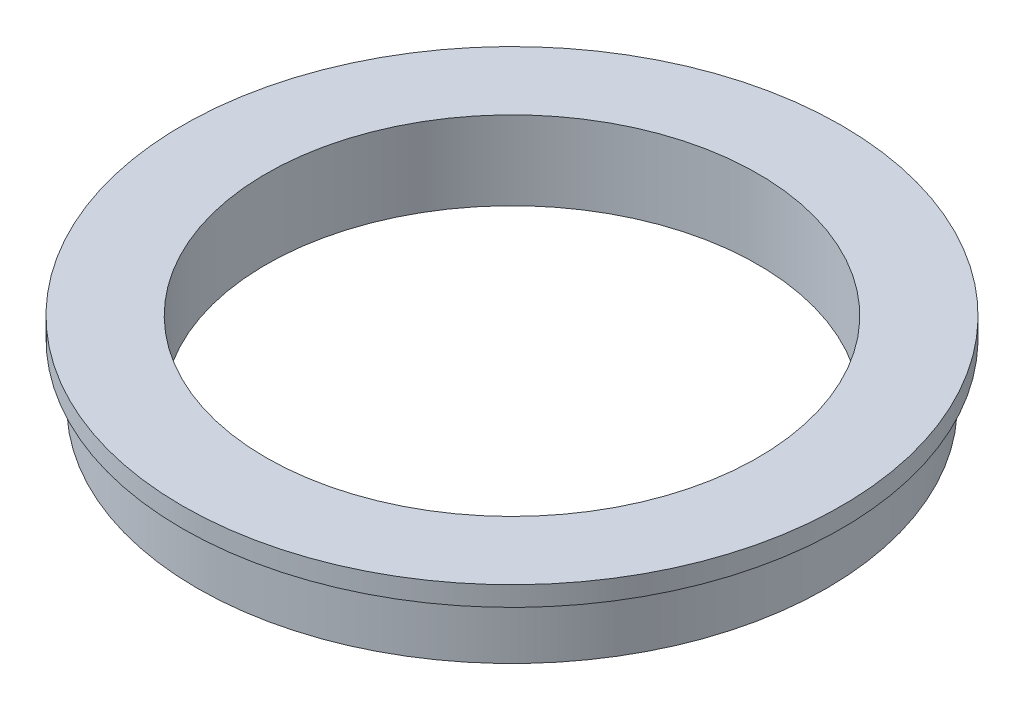
SolidWorks part; units mm, degrees
material "铸造不锈钢"
ref_plane "前视基准面" through (0, 0, 0) normal (0, 0, 1) x (1, 0, 0)
ref_plane "上视基准面" through (0, 0, 0) normal (0, 1, 0) x (1, 0, 0)
ref_plane "右视基准面" through (0, 0, 0) normal (1, 0, 0) x (0, 0, -1)
other "Configuration Table"
sketch "草图1" plane through (0, 0, 0) normal (0, 1, 0) x (1, 0, 0)
  circle A0 centre (0, 0) radius 16
  circle A1 centre (0, 0) radius 12.5
  point P5 (0, -0.2883)
  dimension "D1" = 32
  dimension "D2" = 25
extrude "凸台-拉伸1" add sketch "草图1" along normal blind 4
sketch "草图2" plane through (0, 4, 0) normal (0, 1, 0) x (1, 0, 0)
  circle A0 centre (0, 0) radius 16 construction
  circle A1 centre (0, 0) radius 16
  circle A2 centre (0, 0) radius 16.75
  dimension "D1" = 33.5
extrude "凸台-拉伸2" add sketch "草图2" against normal blind 1
